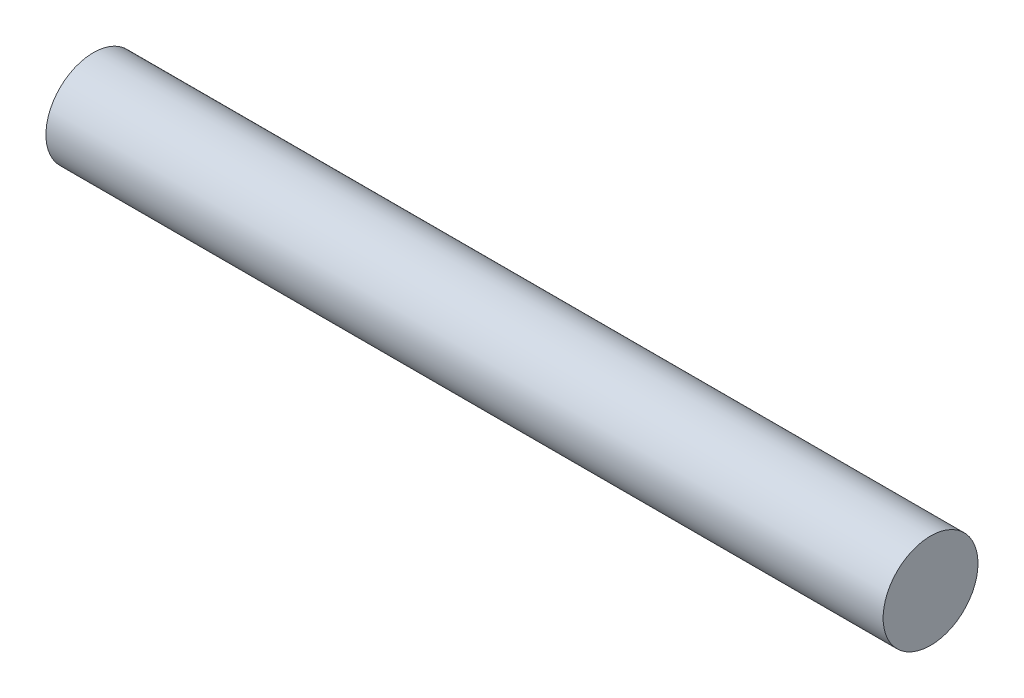
SolidWorks part; units mm, degrees
ref_plane "Front Plane" through (0, 0, 0) normal (0, 0, 1) x (1, 0, 0)
ref_plane "Top Plane" through (0, 0, 0) normal (0, 1, 0) x (1, 0, 0)
ref_plane "Right Plane" through (0, 0, 0) normal (1, 0, 0) x (0, 0, -1)
sketch "Sketch1" plane through (0, 0, 0) normal (1, 0, 0) x (0, 0, -1)
  circle A0 centre (0, 0) radius 8.5
  dimension "D1" = 17
extrude "Boss-Extrude1" add sketch "Sketch1" along normal blind 150 contours A0
